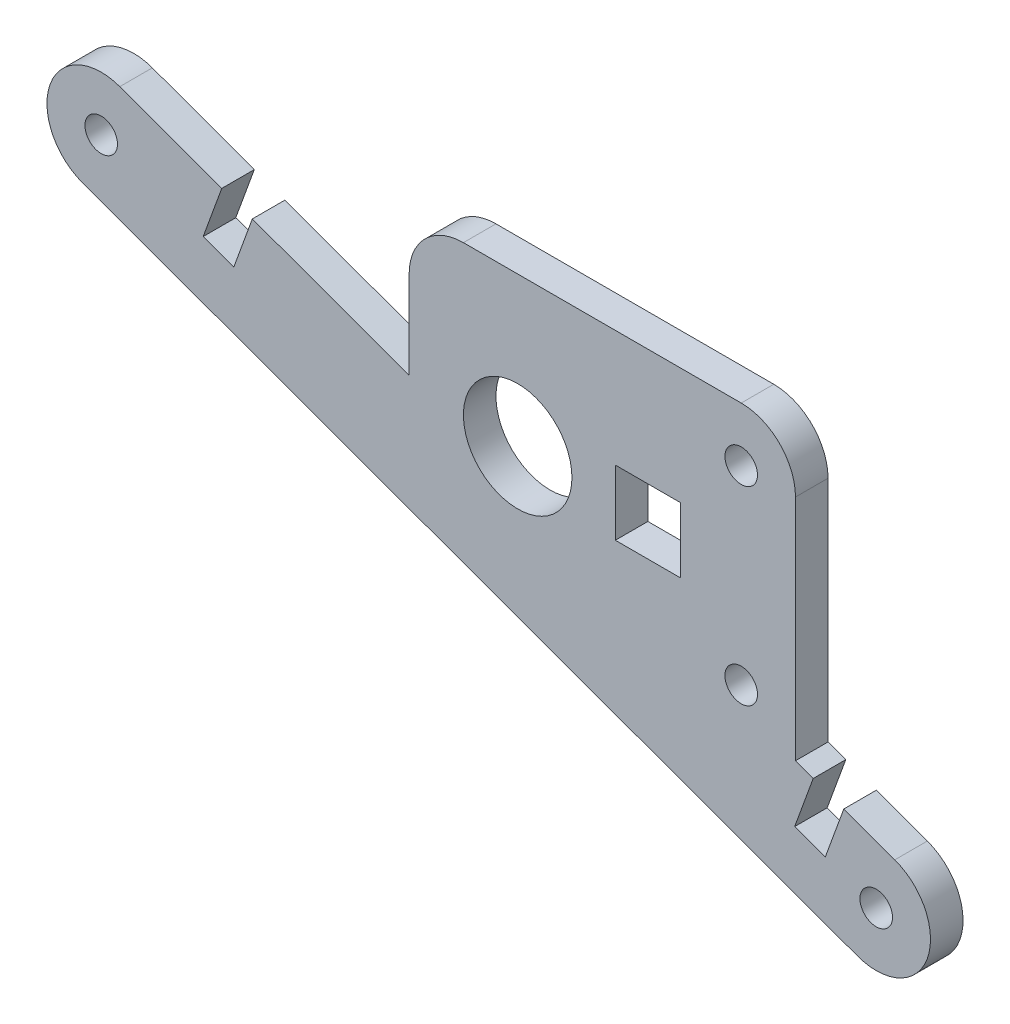
SolidWorks part; units mm, degrees
material "Acrylic (Medium-high impact)"
ref_plane "Front Plane" through (0, 0, 0) normal (0, 0, 1) x (1, 0, 0)
ref_plane "Top Plane" through (0, 0, 0) normal (0, 1, 0) x (1, 0, 0)
ref_plane "Right Plane" through (0, 0, 0) normal (1, 0, 0) x (0, 0, -1)
sketch "Sketch1" plane through (0, 0, 0) normal (0, 0, 1) x (1, 0, 0)
  line L1 (9, -3) -> (15, -3)
  line L2 (9, -3) -> (9, 3)
  line L3 (9, 3) -> (15, 3)
  line L4 (15, -3) -> (15, 3)
  line L5 (9, -3) -> (15, 3) construction
  line L6 (9, 3) -> (15, -3) construction
  line L10 (-76.0289, 19.3717) -> (27.8727, -18.4454) construction
  line L15 (25.6, -12.0314) -> (25.6, 8.75)
  line L16 (20.6, 13.75) -> (-5, 13.75)
  line L17 (0, 0) -> (-45.3227, 0) construction
  line L18 (0, 0) -> (-3.7389, -10.2725) construction
  line L19 (-10, 8.75) -> (-10, 0.66)
  line L20 (-10, 0.66) -> (-36.666, 10.3656)
  line L22 (-40.0862, 0.9687) -> (31.3305, -25.0248)
  line L24 (34.7507, -15.6279) -> (25.6, -12.2973)
  line L25 (25.6, -12.2973) -> (25.6, -12.0314)
  circle A0 centre (0, 0) radius 5
  circle A3 centre (20.6, 8.75) radius 1.5
  circle A4 centre (20.6, -8.75) radius 1.5
  circle A5 centre (-38.3761, 5.6672) radius 1.5
  circle A6 centre (33.0406, -20.3264) radius 1.5
  arc A7 (-10, 8.75) -> (-5, 13.75) centre (-5, 8.75) cw
  arc A8 (25.6, 8.75) -> (20.6, 13.75) centre (20.6, 8.75) ccw
  arc A9 (-36.666, 10.3656) -> (-40.0862, 0.9687) centre (-38.3761, 5.6672) ccw
  arc A10 (31.3305, -25.0248) -> (34.7507, -15.6279) centre (33.0406, -20.3264) ccw
  point P11 (12, 0)
  point P16 (12, -3)
  point P19 (40.6, 0)
  dimension "D1" = 10
  dimension "D3" = 20
  dimension "D4" = 7.8
  dimension "D5" = 3
  dimension "D6" = 3
  dimension "D7" = 38
  dimension "D8" = 3
  dimension "D9" = 3
  dimension "D10" = 20.6
  dimension "D11" = 20.6
  dimension "D12" = 17.5
  dimension "D13" = 8.75
  dimension "D16" = 5.6
  dimension "D22" = 38
  dimension "D18" = 5
  dimension "D19" = 10
  dimension "D23" = 10
  dimension "D24" = 5
  dimension "D27" = 5
  dimension "D28" = 5
  dimension "D29" = 10
  dimension "D14" = 6
  dimension "D15" = 6
  dimension "D17" = 3
  dimension "D21" = 5
  dimension "D25" = 5
  dimension "D26" = 5
extrude "Boss-Extrude1" add sketch "Sketch1" along normal blind 3
sketch "Sketch2" plane through (0, 0, 0) normal (0, 0, -1) x (-1, 0, 0)
  line L0 (10, 0.66) -> (36.666, 10.3656) construction
  line L6 (24.45, 5.9194) -> (27.269, 6.9454)
  line L7 (27.269, 6.9454) -> (28.9792, 2.247)
  line L8 (28.9792, 2.247) -> (26.1601, 1.2209)
  line L9 (26.1601, 1.2209) -> (24.45, 5.9194)
  line L10 (-30.0522, -13.9178) -> (-27.2331, -12.8917)
  line L11 (-34.7507, -15.6279) -> (-25.6, -12.2973) construction
  line L12 (-27.2331, -12.8917) -> (-25.523, -17.5902)
  line L13 (-25.523, -17.5902) -> (-28.3421, -18.6163)
  line L14 (-28.3421, -18.6163) -> (-30.0522, -13.9178)
  circle A0 centre (38.3761, 5.6672) radius 1.5 construction
  circle A1 centre (-33.0406, -20.3264) radius 1.5 construction
  point P0 (27.269, 6.9454)
  dimension "D1" = 3
  dimension "D2" = 5
  dimension "D3" = 10
  dimension "D4" = 3
  dimension "D5" = 5
  dimension "D6" = 5
extrude "Cut-Extrude1" cut sketch "Sketch2" against normal through all
